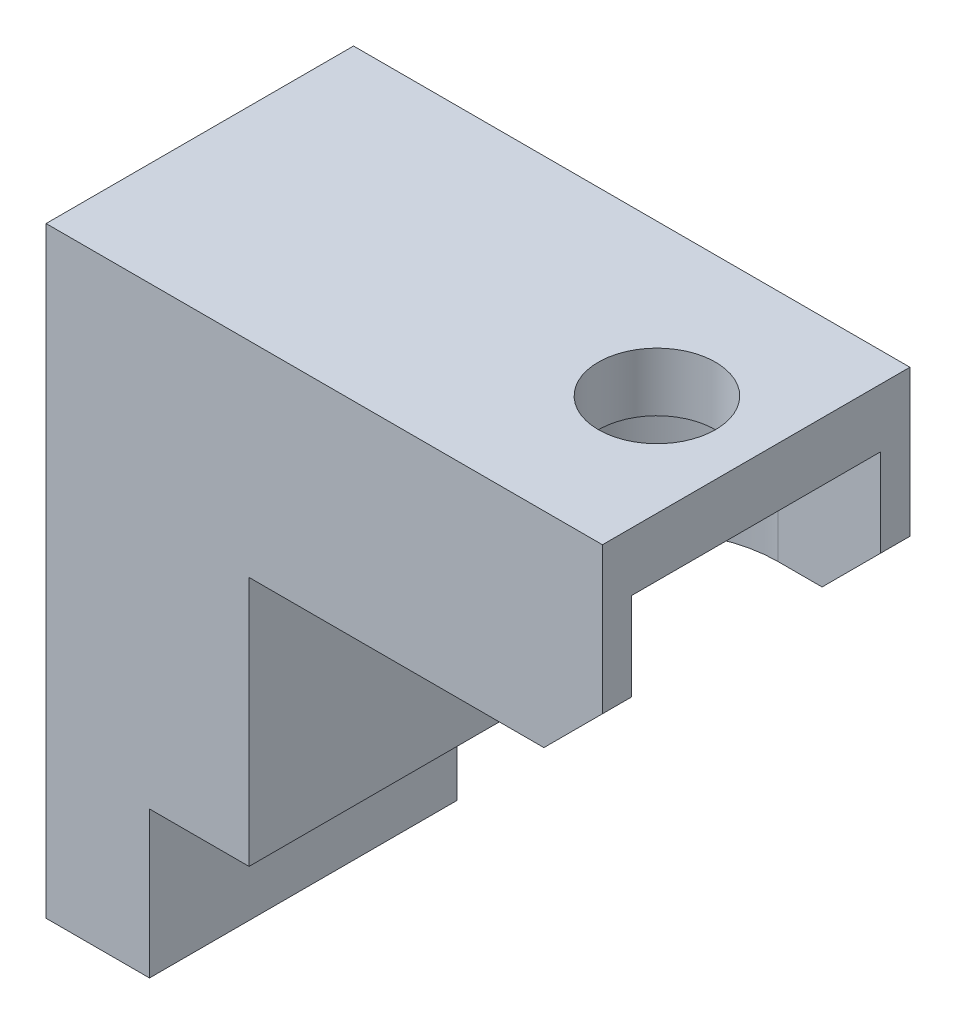
SolidWorks part; units mm, degrees
ref_plane "Face" through (0, 0, 0) normal (0, 0, 1) x (1, 0, 0)
ref_plane "Dessus" through (0, 0, 0) normal (0, 1, 0) x (1, 0, 0)
ref_plane "Droite" through (0, 0, 0) normal (1, 0, 0) x (0, 0, -1)
sketch "Esquisse1" plane through (0, 0, 0) normal (0, 0, 1) x (1, 0, 0)
  line L0 (-55.7193, 49) -> (-67.7876, 49)
  line L1 (-71.1876, 35.4526) -> (-71.1876, 30.4526)
  line L4 (-74.7193, 51) -> (-74.7193, 30.4526)
  line L6 (-67.7876, 35.4526) -> (-67.7876, 49)
  line L7 (-71.1876, 30.4526) -> (-74.7193, 30.4526)
  line L8 (-70.8023, 35.4526) -> (-72.3023, 35.4526) construction
  line L9 (-55.7193, 51) -> (-55.7193, 49)
  line L10 (-71.1876, 35.4526) -> (-67.7876, 35.4526)
  line L13 (-55.7193, 51) -> (-74.7193, 51)
  dimension "D1" = 15.4683
  dimension "D2" = 19
extrude "Extrusion1" add sketch "Esquisse1" along normal mid plane 10.5
sketch "Esquisse2" plane through (0, 49, 0) normal (0, -1, 0) x (1, 0, 0)
  line L0 (-55.7193, 5.25) -> (-55.7193, -5.25) construction
  line L1 (-55.7193, 5.25) -> (-69.8023, 5.25)
  line L2 (-55.7193, 5.25) -> (-55.7193, 4.25)
  line L3 (-55.7193, 4.25) -> (-59.2193, 4.25)
  line L4 (-69.8023, -5.25) -> (-69.8023, 5.25)
  line L6 (-55.7193, -5.25) -> (-69.8023, -5.25)
  line L7 (-55.7193, -5.25) -> (-55.7193, -4.25)
  line L8 (-55.7193, -4.25) -> (-59.2193, -4.25)
  arc A0 (-59.2193, -4.25) -> (-59.2193, 4.25) centre (-59.2193, 0) cw
  dimension "D1" = 1
  dimension "D2" = 1
  dimension "D3" = 3.5
extrude "Extrusion2" add sketch "Esquisse2" along normal blind 5
sketch "Esquisse3" plane through (0, 51, 0) normal (0, 1, 0) x (-1, 0, 0)
  circle A0 centre (59.1909, -0.0816) radius 2
  dimension "D1" = 4
extrude "Enlèv. mat.-Extru.1" cut sketch "Esquisse3" against normal up to surface (2 mm away) up to face at (-58.5318, 49, 0)
chamfer "Chanfrein1" distance 2 angle 45 2 edges at (-55.7193, 44, 4.75) (-55.7193, 44, -4.75)
